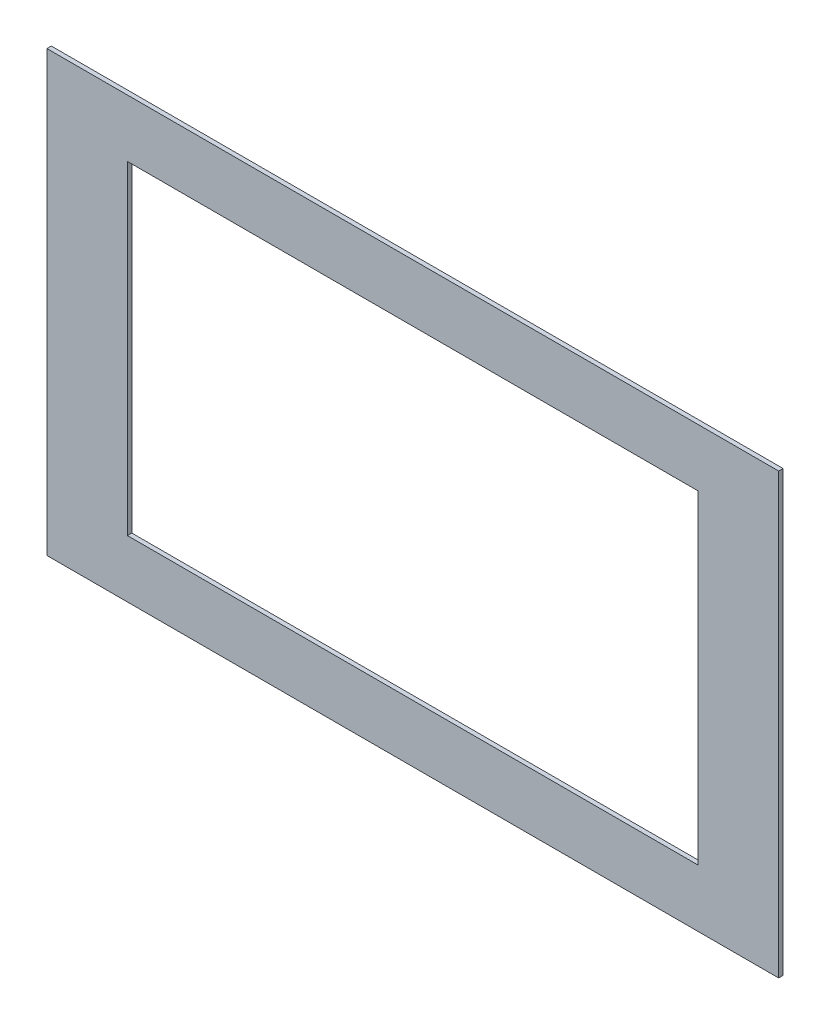
SolidWorks part; units mm, degrees
material "AÇO 1020"
ref_plane "Front Plane" through (0, 0, 0) normal (0, 0, 1) x (1, 0, 0)
ref_plane "Top Plane" through (0, 0, 0) normal (0, 1, 0) x (1, 0, 0)
ref_plane "Right Plane" through (0, 0, 0) normal (1, 0, 0) x (0, 0, -1)
sketch "Sketch1" plane through (0, 0, 0) normal (0, 0, 1) x (1, 0, 0)
  line L1 (125, 75) -> (-125, 75)
  line L2 (125, 75) -> (125, -75)
  line L3 (125, -75) -> (-125, -75)
  line L4 (-125, 75) -> (-125, -75)
  line L5 (0, -75) -> (0, 75) construction
  line L6 (125, 0) -> (-125, 0) construction
  point P0 (0, 0)
  dimension "D1" = 250
  dimension "D2" = 150
extrude "Extrude1" add sketch "Sketch1" along normal blind 1.5
sketch "Sketch2" plane through (0, 0, 1.5) normal (0, 0, 1) x (1, 0, 0)
  line L1 (97.5, 55.35) -> (-97.5, 55.35)
  line L2 (97.5, 55.35) -> (97.5, -55.35)
  line L3 (97.5, -55.35) -> (-97.5, -55.35)
  line L4 (-97.5, 55.35) -> (-97.5, -55.35)
  line L5 (0, -55.35) -> (0, 55.35) construction
  line L6 (97.5, 0) -> (-97.5, 0) construction
  point P0 (0, 0)
  dimension "D1" = 110.7
  dimension "D2" = 195
extrude "Extrude2" cut sketch "Sketch2" against normal up to surface (1.5 mm away) up to face at (0, 0, 0)
